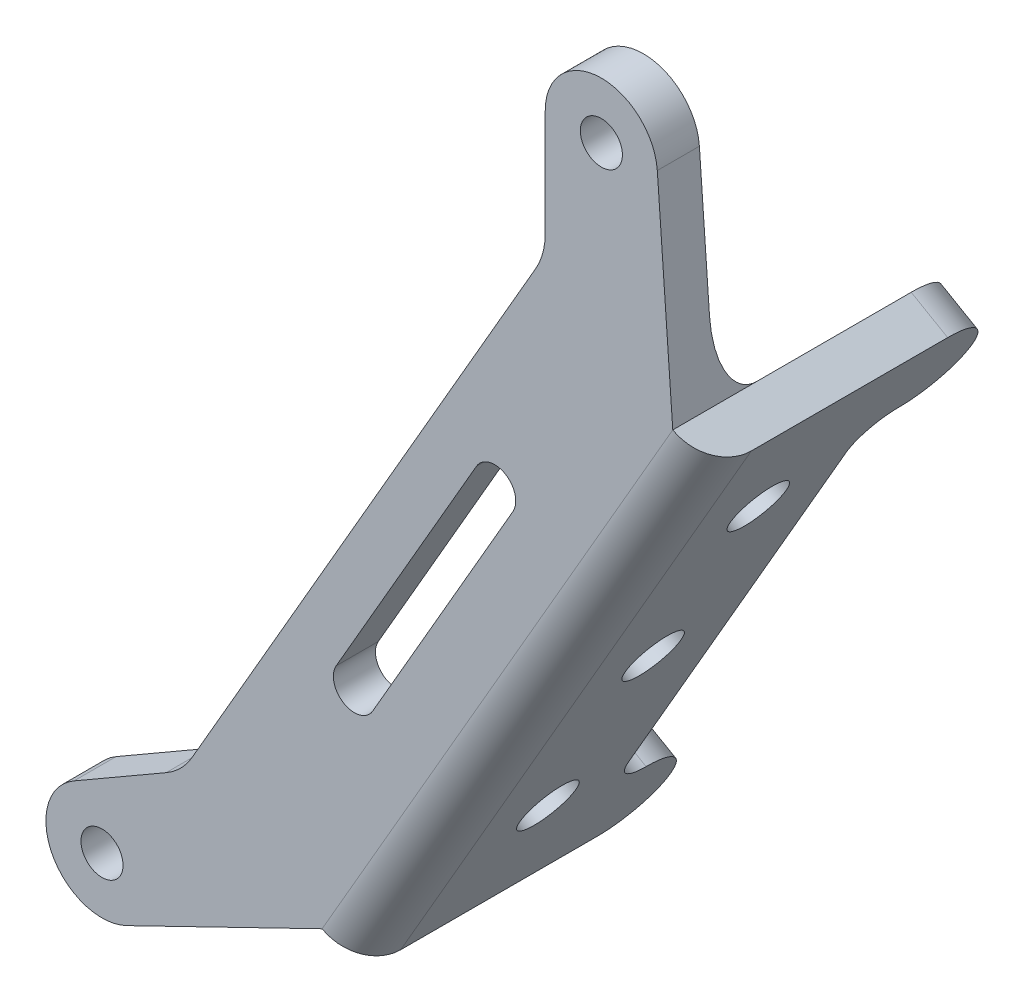
SolidWorks part; units mm, degrees
ref_plane "前视基准面" through (0, 0, 0) normal (0, 0, 1) x (1, 0, 0)
ref_plane "上视基准面" through (0, 0, 0) normal (0, 1, 0) x (1, 0, 0)
ref_plane "右视基准面" through (0, 0, 0) normal (1, 0, 0) x (0, 0, -1)
sketch "草图1" plane through (0, 0, 0) normal (0, 0, 1) x (1, 0, 0)
  line L0 (74.7353, -81.9464) -> (82.4674, -77.4823)
  line L1 (82.4674, -77.4823) -> (108.3353, -32.6777)
  line L2 (95.4014, -55.08) -> (0, 0) construction
  line L3 (0, 0) -> (126.2146, 0) construction
  line L4 (78.4839, -89.0081) -> (92.4276, -82.2306)
  line L5 (92.4276, -82.2306) -> (117.4276, -38.9294)
  line L7 (95.4014, -55.08) -> (104.9276, -60.58) construction
  line L8 (116.3252, -23.4651) -> (117.4276, -38.9294)
  line L9 (108.3353, -23.7495) -> (108.3353, -32.6777)
  circle A0 centre (76.7353, -85.4105) radius 4
  circle A1 centre (112.3353, -23.7495) radius 1.5
  circle A2 centre (112.3353, -23.7495) radius 4
  circle A3 centre (76.7353, -85.4105) radius 1.5
  circle A4 centre (112.3353, -23.7495) radius 4.3
  circle A5 centre (76.7353, -85.4105) radius 4.3
  dimension "D3" = 8
  dimension "D1" = 30
  dimension "D2" = 150
  dimension "D4" = 50
  dimension "D5" = 1
  dimension "D6" = 11
extrude "凸台-拉伸1" add sketch "草图1" along normal blind 3 contours A5 L4 L5 L8 A4 L9 L1 L0 | A4 A1 | A5 A3 | L4 A5 L0 A0 | L9 A4 L8 A2
sketch "草图2" plane through (0, 0, 3) normal (0, 0, 1) x (1, 0, 0)
  line L0 (94.7315, -66.2403) -> (104.7315, -48.9197) construction
  line L3 (93.4324, -65.4903) -> (103.4324, -48.1697)
  line L4 (96.0305, -66.9903) -> (106.0305, -49.6697)
  line L5 (104.9276, -60.58) -> (99.7315, -57.58) construction
  line L6 (92.4276, -82.2306) -> (117.4276, -38.9294) construction
  line L7 (82.4674, -77.4823) -> (108.3353, -32.6777) construction
  arc A2 (93.4324, -65.4903) -> (96.0305, -66.9903) centre (94.7315, -66.2403) ccw
  arc A3 (106.0305, -49.6697) -> (103.4324, -48.1697) centre (104.7315, -48.9197) ccw
  point P2 (99.7315, -57.58)
  dimension "D3" = 1.5
  dimension "D1" = 20
  dimension "D2" = 3.5
extrude "切除-拉伸1" cut sketch "草图2" against normal through all
sketch "草图3" plane through (104.9276, -60.58, 0) normal (0.866, -0.5, 0) x (0, 0, -1)
  line L0 (-3, -25) -> (0, -25) construction
  line L1 (-3, 25) -> (27, 25)
  line L2 (-3, 25) -> (-3, -25)
  line L3 (-3, -25) -> (27, -25)
  line L4 (27, 25) -> (27, -25)
  line L5 (-3, -37.8413) -> (-3, -25) construction
  dimension "D1" = 30
extrude "凸台-拉伸2" add sketch "草图3" along normal blind 3
fillet "圆角1" radius 3 2 edges at (107.5257, -62.08, 3) (104.9276, -60.58, 0)
sketch "草图4" plane through (107.5257, -62.08, 0) normal (0.866, -0.5, 0) x (0, 0, -1)
  line L0 (27, 0) -> (-24.1005, 0) construction
  line L1 (27, -25) -> (27, 25) construction
  line L2 (14, -25) -> (14, -21.5) construction
  line L3 (0, 25) -> (-3, 25) construction
  line L4 (-3, 25) -> (3, 25) construction
  line L5 (-3, -25) -> (-3, 25) construction
  line L6 (-3, 25) -> (14, 25)
  line L7 (14, 25) -> (14, 21.5) construction
  line L8 (14, 21.5) -> (14, 15.5) construction
  line L9 (11.5, 15.5) -> (11.5, -15.5)
  line L11 (14, -21.5) -> (14, -15.5) construction
  line L12 (-3, -25) -> (14, -25)
  line L21 (27, 25) -> (0, 25)
  line L22 (0, 25) -> (0, -25)
  line L23 (0, -25) -> (27, -25)
  line L24 (27, -25) -> (27, 25)
  line L25 (27, 25) -> (0, 25)
  line L26 (0, 25) -> (0, -25)
  line L27 (0, -25) -> (27, -25)
  line L28 (27, -25) -> (27, 25)
  arc A1 (14, 18) -> (11.5, 15.5) centre (14, 15.5) ccw
  arc A2 (14, -18) -> (14, -25) centre (14, -21.5) cw
  circle A4 centre (5.5, 0) radius 2
  circle A5 centre (5.5, 15) radius 2
  circle A6 centre (5.5, -15) radius 2
  arc A7 (14, 18) -> (14, 25) centre (14, 21.5) ccw
  circle A8 centre (5.5, -15) radius 2
  arc A9 (14, -18) -> (11.5, -15.5) centre (14, -15.5) cw
  point P28 (11.5, 0)
  dimension "D1" = 17
  dimension "D3" = 6
  dimension "D6" = 4
  dimension "D4" = 7
  dimension "D2" = 5
  dimension "D8" = 15
  dimension "D5" = 0
extrude "切除-拉伸2" cut sketch "草图4" against normal through all
fillet "圆角2" radius 5 2 edges at (82.4674, -77.4823, 1.5) (108.3353, -32.6777, 1.5)
